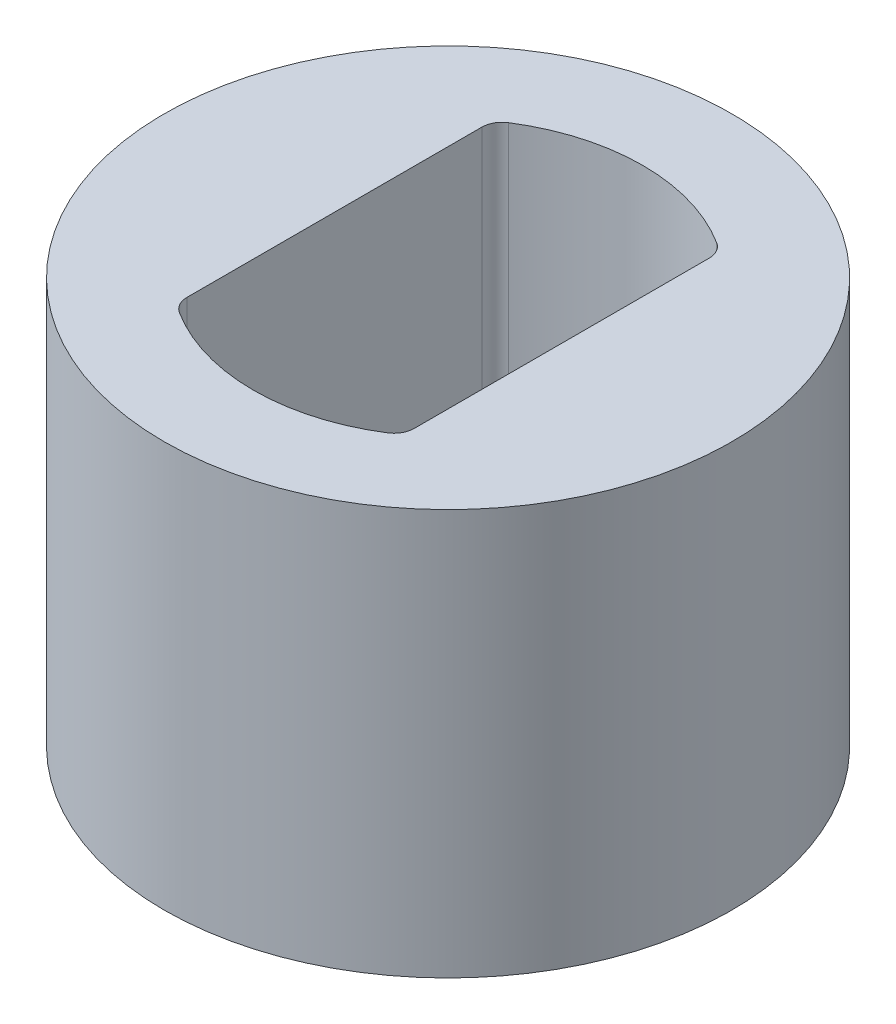
SolidWorks part; units mm, degrees
ref_plane "Front Plane" through (0, 0, 0) normal (0, 0, 1) x (1, 0, 0)
ref_plane "Top Plane" through (0, 0, 0) normal (0, 1, 0) x (1, 0, 0)
ref_plane "Right Plane" through (0, 0, 0) normal (1, 0, 0) x (0, 0, -1)
sketch "Sketch1" plane through (0, 0, 0) normal (0, 1, 0) x (1, 0, 0)
  circle A0 centre (0, 0) radius 3.5
  dimension "D1" = 7
extrude "Boss-Extrude1" add sketch "Sketch1" along normal blind 5
sketch "Sketch2" plane through (0, 5, 0) normal (0, 1, 0) x (1, 0, 0)
  line L0 (1.4, 1.9494) -> (1.4, -1.9494)
  line L1 (-1.4, 1.9494) -> (-1.4, -1.9494)
  circle A0 centre (0, 0) radius 2.4
  dimension "D1" = 4.8
  dimension "D2" = 2.8
extrude "Cut-Extrude1" cut sketch "Sketch2" against normal blind 5 contours L0 A0 L1
fillet "Fillet1" radius 0.25 4 edges at (1.4, 2.5, -1.9494) (1.4, 2.5, 1.9494) (-1.4, 2.5, 1.9494) (-1.4, 2.5, -1.9494)
